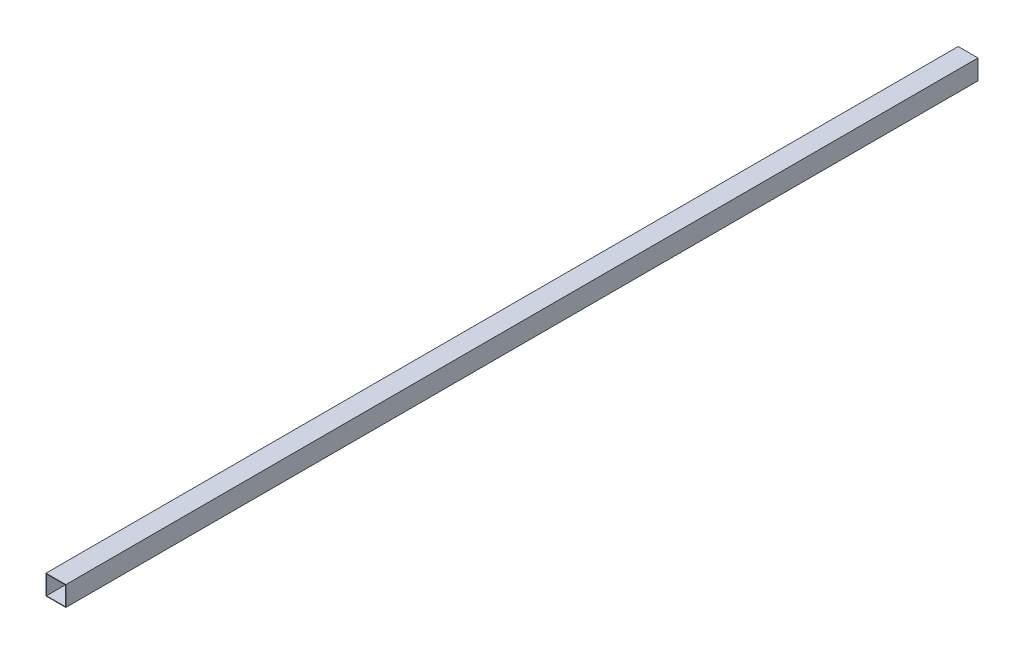
SolidWorks part; units mm, degrees
material "1100-H18 棒材(SS)"
ref_plane "前视基准面" through (0, 0, 0) normal (0, 0, 1) x (1, 0, 0)
ref_plane "上视基准面" through (0, 0, 0) normal (0, 1, 0) x (1, 0, 0)
ref_plane "右视基准面" through (0, 0, 0) normal (1, 0, 0) x (0, 0, -1)
other "Configuration Table"
sketch "草图1" plane through (0, 0, 0) normal (0, 0, 1) x (1, 0, 0)
  line L1 (0, 0) -> (40, 0)
  line L2 (0, 0) -> (0, 40)
  line L3 (0, 40) -> (40, 40)
  line L4 (40, 0) -> (40, 40)
  line L5 (1, 1) -> (39, 1)
  line L6 (1, 1) -> (1, 39)
  line L7 (1, 39) -> (39, 39)
  line L8 (39, 1) -> (39, 39)
  dimension "D1" = 40
  dimension "D2" = 40
  dimension "D3" = 1
  dimension "D4" = 1
  dimension "D5" = 1
  dimension "D6" = 1
extrude "凸台-拉伸1" add sketch "草图1" along normal blind 1840
